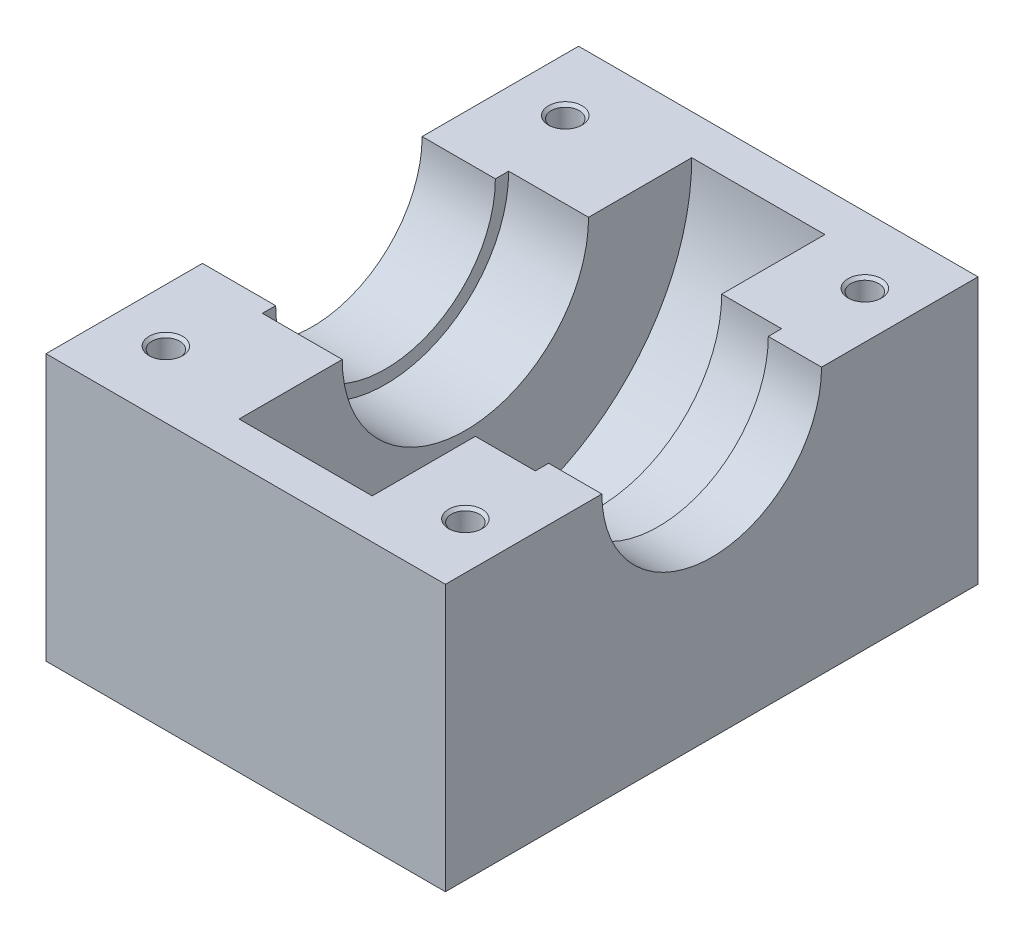
SolidWorks part; units mm, degrees
ref_plane "Piano frontale" through (0, 0, 0) normal (0, 0, 1) x (1, 0, 0)
ref_plane "Piano superiore" through (0, 0, 0) normal (0, 1, 0) x (1, 0, 0)
ref_plane "Piano destro" through (0, 0, 0) normal (1, 0, 0) x (0, 0, -1)
sketch "Schizzo1" plane through (0, 0, 0) normal (0, 1, 0) x (1, 0, 0)
  line L1 (-30, -40) -> (30, -40)
  line L2 (-30, -40) -> (-30, 40)
  line L3 (-30, 40) -> (30, 40)
  line L4 (30, -40) -> (30, 40)
  line L5 (-30, -40) -> (30, 40) construction
  line L6 (-30, 40) -> (30, -40) construction
  point P0 (0, 0)
  dimension "D1" = 60
  dimension "D2" = 80
extrude "Estrusione-Estrusione1" add sketch "Schizzo1" along normal blind 40
sketch "Schizzo2" plane through (30, 0, 0) normal (1, 0, 0) x (0, 0, -1)
  line L0 (-40, 40) -> (40, 40) construction
  line L1 (-16.5, 40) -> (16.5, 40)
  arc A0 (-16.5, 40) -> (16.5, 40) centre (0, 40) ccw
  dimension "D1" = 33
extrude "Taglio-Estrusione1" cut sketch "Schizzo2" against normal up to next
sketch "Schizzo3" plane through (30, 0, 0) normal (1, 0, 0) x (0, 0, -1)
  line L1 (16.5, 40) -> (40, 40) construction
  line L3 (-40, 40) -> (-16.5, 40) construction
  line L5 (16.5, 40) -> (18.5, 40)
  line L6 (-18.5, 40) -> (-16.5, 40)
  arc A2 (-16.5, 40) -> (16.5, 40) centre (0, 40) ccw construction
  arc A3 (-16.5, 40) -> (16.5, 40) centre (0, 40) ccw
  arc A4 (-18.5, 40) -> (18.5, 40) centre (0, 40) ccw
  dimension "D1" = 37
extrude "Taglio-Estrusione2" cut sketch "Schizzo3" against normal blind 9 from offset 8 offset against normal yes
sketch "Schizzo4" plane through (-30, 0, 0) normal (-1, 0, 0) x (0, 0, 1)
  line L0 (16.5, 40) -> (40, 40) construction
  line L1 (-40, 40) -> (-16.5, 40) construction
  line L2 (16.5, 40) -> (18.5, 40)
  line L3 (-18.5, 40) -> (-16.5, 40)
  arc A0 (-16.5, 40) -> (16.5, 40) centre (0, 40) ccw construction
  arc A1 (-16.5, 40) -> (16.5, 40) centre (0, 40) ccw
  arc A2 (-18.5, 40) -> (18.5, 40) centre (0, 40) ccw
  dimension "D1" = 37
extrude "Taglio-Estrusione3" cut sketch "Schizzo4" against normal blind 12 from offset 11 offset against normal yes
sketch "Schizzo5" plane through (-30, 0, 0) normal (-1, 0, 0) x (0, 0, 1)
  line L0 (16.5, 40) -> (40, 40) construction
  line L1 (-40, 40) -> (-16.5, 40) construction
  line L2 (16.5, 40) -> (34, 40)
  line L3 (-34, 40) -> (-16.5, 40)
  arc A0 (-16.5, 40) -> (16.5, 40) centre (0, 40) ccw construction
  arc A1 (-16.5, 40) -> (16.5, 40) centre (0, 40) ccw
  arc A2 (-34, 40) -> (34, 40) centre (0, 40) ccw
  dimension "D1" = 68
extrude "Taglio-Estrusione4" cut sketch "Schizzo5" against normal up to surface (20 mm away) from surface at -23 up to face at (13, 31.25, 0) starting at face at (-7, 31.25, 0)
sketch "Schizzo6" plane through (0, 40, 0) normal (0, 1, 0) x (1, 0, 0)
  line L0 (-30, 0) -> (30, 0) construction
  line L1 (0.5, -40) -> (0.5, 40) construction
  line L2 (-30, 16.5) -> (-30, -16.5) construction
  line L6 (-30, -40) -> (30, -40) construction
  line L7 (-30, -16.5) -> (-30, -40) construction
  line L9 (30, 40) -> (-30, 40) construction
  point P0 (-22, -30)
  point P4 (0, 0)
  point P8 (0, 0)
  point P11 (0, 40)
  point P12 (0, 0)
  point P17 (-22, 30)
  point P18 (23, 30)
  point P19 (23, -30)
  point P20 (0, 0)
  point P23 (0, 0)
  dimension "D3" = 0.5
  dimension "D1" = 10
  dimension "D2" = 8
hole_wizard "Foro filettato M5x0.8-1" positions "Schizzo3D1" profile "Schizzo7" tap size "M5x0.8" standard "Ansi Metric"
sketch3d "Schizzo3D1"
  point P0 (-22, 40, -30)
  point P3 (23, 40, -30)
  point P6 (-22, 40, 30)
  point P9 (23, 40, 30)
cosmetic thread "Filettatura del foro1" parameters "D1"=10, "D2"=5
cosmetic thread "Filettatura del foro2" parameters "D1"=10, "D2"=5
cosmetic thread "Filettatura del foro3" parameters "D1"=10, "D2"=5
cosmetic thread "Filettatura del foro4" parameters "D1"=10, "D2"=5
sketch "Schizzo7" plane through (-22, 40, -30) normal (1, 0, 0) x (0, 0, 1)
  line L0 (0, 0) -> (0, 14)
  line L1 (0, 14) -> (2.1, 12.7382)
  line L2 (2.1, 12.7382) -> (2.1, 0.425)
  line L3 (2.1, 0.425) -> (2.525, 0)
  line L5 (2.525, 0) -> (0, 0)
  line L6 (-2.1, 0.425) -> (-2.525, 0) construction
  line L10 (0, 14) -> (-2.1, 12.7382) construction
  line L11 (0, -6.35) -> (0, 107.95) construction
  dimension "Tap Drill Dia." = 4.2
  dimension "Tap Drill Depth" = 14
  dimension "Near C'Sink Dia." = 5.05
  dimension "Near C'Sink Angle" = 90
  dimension "Drill Angle" = 118
